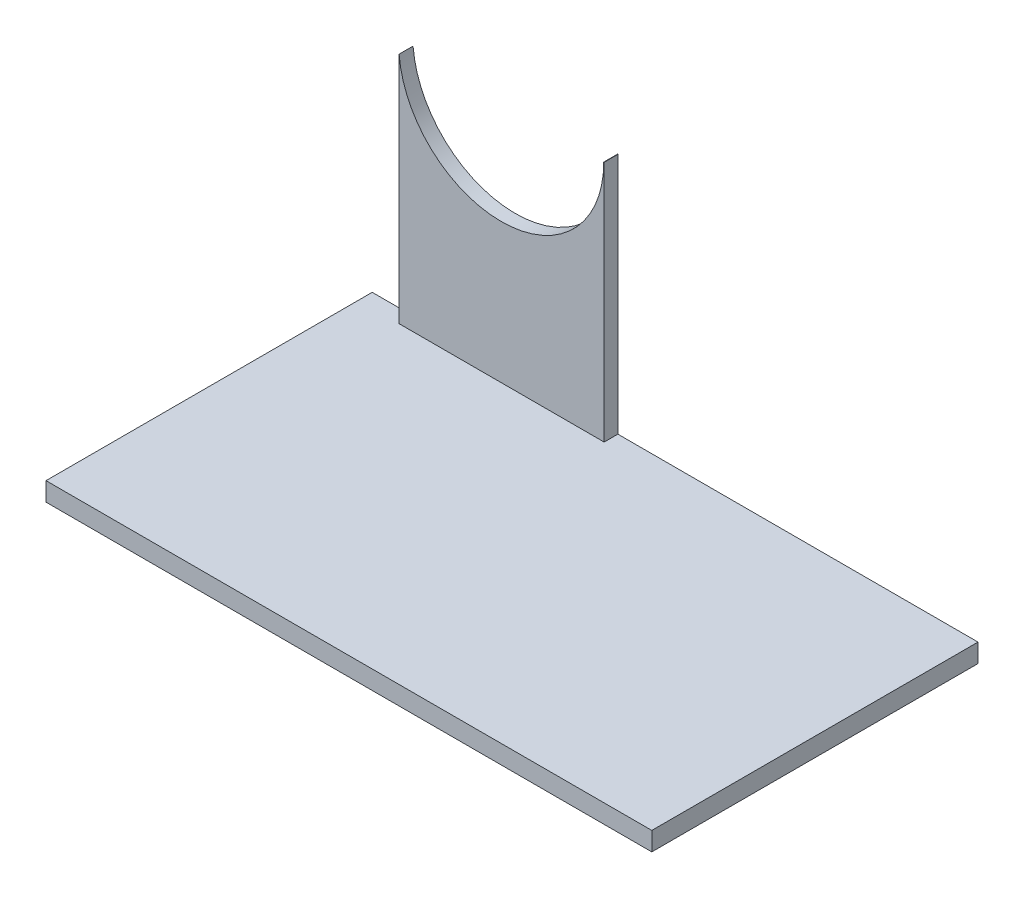
SolidWorks part; units mm, degrees
ref_plane "Front Plane" through (0, 0, 0) normal (0, 0, 1) x (1, 0, 0)
ref_plane "Top Plane" through (0, 0, 0) normal (0, 1, 0) x (1, 0, 0)
ref_plane "Right Plane" through (0, 0, 0) normal (1, 0, 0) x (0, 0, -1)
sketch "Sketch1" plane through (0, 0, 0) normal (0, 1, 0) x (1, 0, 0)
  line L1 (-23.7949, 15.5897) -> (41.2051, 15.5897)
  line L2 (-23.7949, 15.5897) -> (-23.7949, -19.4103)
  line L3 (-23.7949, -19.4103) -> (41.2051, -19.4103)
  line L4 (41.2051, 15.5897) -> (41.2051, -19.4103)
  point P4 (0, 0)
  point P5 (0, 0)
  point P6 (0, 0)
  dimension "D1" = 65
  dimension "D2" = 35
sketch "Sketch4" plane through (0, 0, 0) normal (0, 1, 0) x (1, 0, 0)
  line L1 (-23.7949, 15.5897) -> (41.2051, 15.5897)
  line L2 (-23.7949, 15.5897) -> (-23.7949, -19.4103)
  line L3 (-23.7949, -19.4103) -> (41.2051, -19.4103)
  line L4 (41.2051, 15.5897) -> (41.2051, -19.4103)
extrude "Boss-Extrude1" add sketch "Sketch4" along normal offset from surface (2 mm away) 2 up to plane "Top Plane"
sketch "Sketch9" plane through (0, 2, 0) normal (0, 1, 0) x (1, 0, 0)
  line L1 (-19.4375, 15.6168) -> (2.5656, 15.6168)
  line L2 (-19.4375, 15.6168) -> (-19.4375, 14.1168)
  line L3 (-19.4375, 14.1168) -> (2.5656, 14.1168)
  line L4 (2.5656, 15.6168) -> (2.5656, 14.1168)
  dimension "D1" = 22.0031
  dimension "D2" = 1.5
extrude "Boss-Extrude15" add sketch "Sketch9" along normal offset from surface (26 mm away) 26 up to face at (8.7051, 2, 1.9103) offset beyond the face yes
sketch "Sketch11" plane through (0, 0, -15.6168) normal (0, 0, -1) x (-1, 0, 0)
  circle A0 centre (8.4766, 27.9721) radius 11
  point P2 (17.1256, 33.0208)
  dimension "D1" = 22
extrude "Cut-Extrude1" cut sketch "Sketch11" against normal through all
